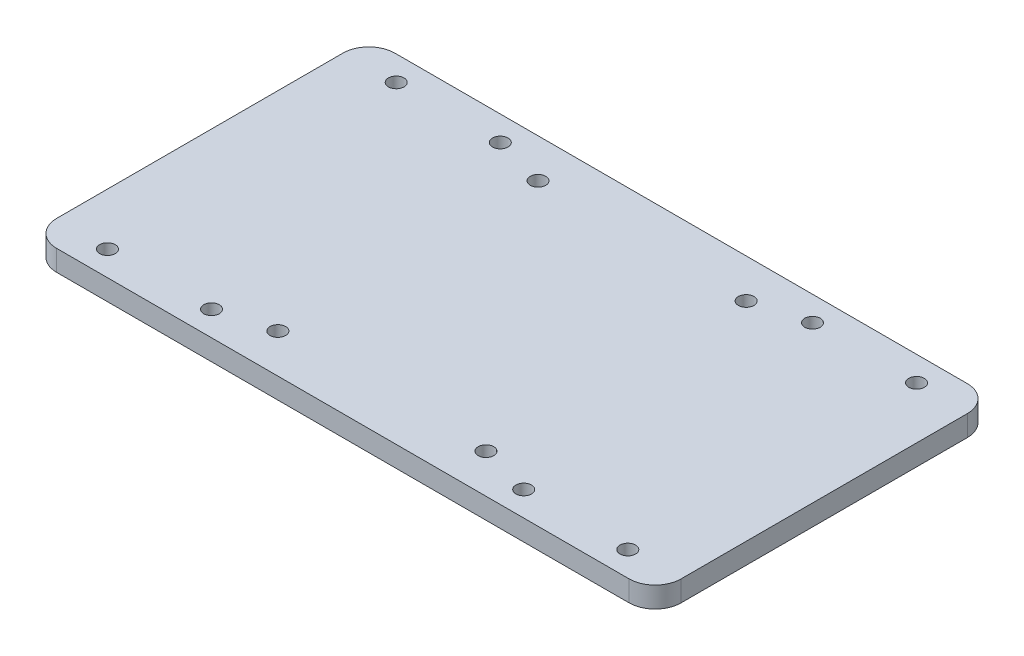
SolidWorks part; units mm, degrees
ref_plane "前视基准面" through (0, 0, 0) normal (0, 0, 1) x (1, 0, 0)
ref_plane "上视基准面" through (0, 0, 0) normal (0, 1, 0) x (1, 0, 0)
ref_plane "右视基准面" through (0, 0, 0) normal (1, 0, 0) x (0, 0, -1)
other "Configuration Table"
sketch "草图1" plane through (0, 0, 0) normal (0, 1, 0) x (1, 0, 0)
  line L1 (-60, -32.5) -> (60, -32.5)
  line L2 (-60, -32.5) -> (-60, 32.5)
  line L3 (-60, 32.5) -> (60, 32.5)
  line L4 (60, -32.5) -> (60, 32.5)
  line L5 (-60, -32.5) -> (60, 32.5) construction
  line L6 (-60, 32.5) -> (60, -32.5) construction
  point P0 (0, 0)
  dimension "D1" = 65
  dimension "D2" = 120
extrude "凸台-拉伸1" add sketch "草图1" along normal blind 4
sketch "草图2" plane through (0, 4, 0) normal (0, 1, 0) x (1, 0, 0)
  line L1 (30, 27.75) -> (50, 27.75) construction
  line L2 (30, 27.75) -> (30, -27.75) construction
  line L3 (30, -27.75) -> (50, -27.75) construction
  line L4 (50, 27.75) -> (50, -27.75) construction
  line L5 (60, -32.5) -> (60, 32.5) construction
  line L6 (0, 0) -> (30, 0) construction
  circle A0 centre (50, -27.75) radius 1.5
  circle A1 centre (50, 27.75) radius 1.5
  circle A2 centre (30, 27.75) radius 1.5
  circle A3 centre (30, -27.75) radius 1.5
  dimension "D5" = 3
  dimension "D1" = 20
  dimension "D2" = 55.5
  dimension "D4" = 10
extrude "切除-拉伸1" cut sketch "草图2" against normal blind 4
mirror "镜向2" about plane through (0, 0, 0) normal (1, 0, 0) of "切除-拉伸1"
fillet "圆角1" radius 5 4 edges at (-60, 2, 32.5) (60, 2, 32.5) (60, 2, -32.5) (-60, 2, -32.5)
sketch "草图3" plane through (0, 4, 0) normal (0, 1, 0) x (1, 0, 0)
  line L0 (-20, 25) -> (20, 25) construction
  line L1 (-20, -25) -> (20, -25) construction
  line L2 (-20, -25) -> (-20, 25) construction
  line L3 (-20, 25) -> (20, 25) construction
  line L4 (20, -25) -> (20, 25) construction
  line L5 (-20, -25) -> (20, 25) construction
  line L6 (-20, 25) -> (20, -25) construction
  line L7 (-20, 25) -> (-20, -25) construction
  circle A0 centre (-20, 25) radius 1.5
  circle A1 centre (20, 25) radius 1.5
  circle A2 centre (20, -25) radius 1.5
  circle A3 centre (-20, -25) radius 1.5
  point P0 (0, 0)
  point P7 (0, 0)
  dimension "D3" = 3
  dimension "D4" = 2
  dimension "D1" = 50
  dimension "D2" = 40
  dimension "D6" = 40
  dimension "D5" = 2
extrude "切除-拉伸2" cut sketch "草图3" against normal blind 4
